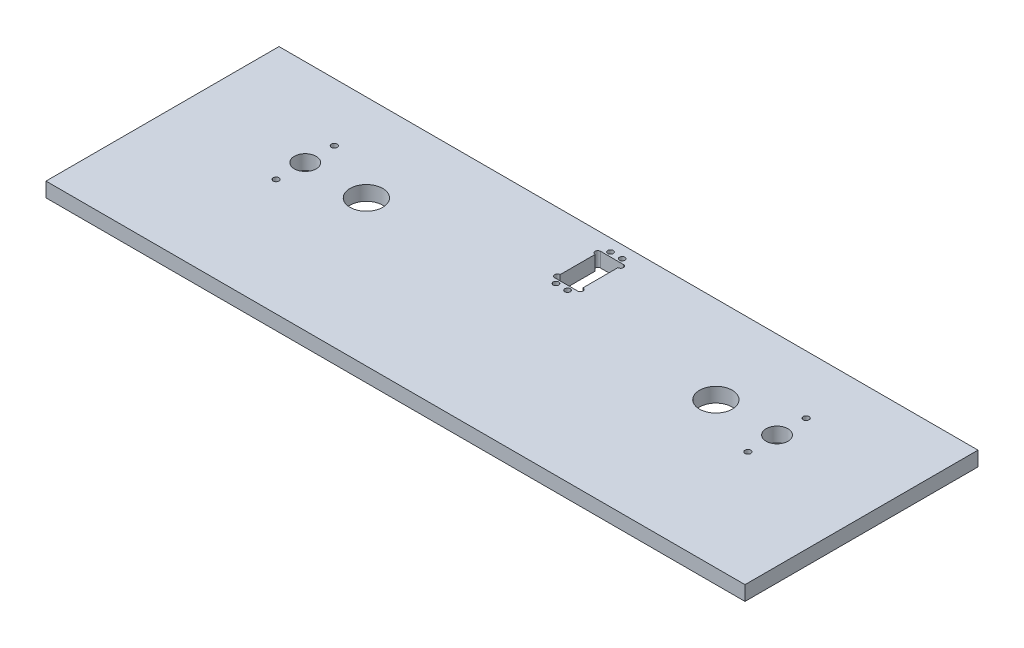
SolidWorks part; units mm, degrees
ref_plane "Front Plane" through (0, 0, 0) normal (0, 0, 1) x (1, 0, 0)
ref_plane "Top Plane" through (0, 0, 0) normal (0, 1, 0) x (1, 0, 0)
ref_plane "Right Plane" through (0, 0, 0) normal (1, 0, 0) x (0, 0, -1)
sketch "Sketch1" plane through (0, 0, 0) normal (0, 1, 0) x (1, 0, 0)
  line L0 (-53.34, 0) -> (-53.34, 25.4) construction
  line L1 (-53.34, 0) -> (-53.34, -25.4) construction
  line L2 (152.4, 51.221) -> (152.4, -51.2649) construction
  line L3 (-101.4095, -20.0025) -> (-101.4095, -9.652) construction
  line L4 (-111.379, -40.005) -> (-91.44, -40.005) construction
  line L5 (-111.379, -40.005) -> (-111.379, 0) construction
  line L6 (-111.379, 0) -> (-91.44, 0) construction
  line L7 (-91.44, -40.005) -> (-91.44, 0) construction
  line L8 (-111.379, -40.005) -> (-91.44, 0) construction
  line L9 (-111.379, 0) -> (-91.44, -40.005) construction
  line L10 (-106.4895, -43.815) -> (-96.3295, -43.815) construction
  line L11 (-106.4895, -43.815) -> (-106.4895, 3.81) construction
  line L12 (-106.4895, 3.81) -> (-96.3295, 3.81) construction
  line L13 (-96.3295, -43.815) -> (-96.3295, 3.81) construction
  line L14 (-106.4895, -43.815) -> (-96.3295, 3.81) construction
  line L15 (-106.4895, 3.81) -> (-96.3295, -43.815) construction
  line L16 (-82.3595, 11.7475) -> (-120.4595, 11.7475) construction
  line L17 (-82.3595, 11.7475) -> (-82.3595, -51.7525) construction
  line L18 (-82.3595, -51.7525) -> (-120.4595, -51.7525) construction
  line L19 (-120.4595, 11.7475) -> (-120.4595, -51.7525) construction
  line L21 (-152.4, 76.2) -> (152.4, 76.2)
  line L22 (-152.4, 76.2) -> (-152.4, -127)
  line L23 (-152.4, -127) -> (152.4, -127)
  line L24 (152.4, 76.2) -> (152.4, -127)
  circle A0 centre (0, 0) radius 14.2875
  circle A1 centre (0, 0) radius 45.72 construction
  circle A2 centre (-53.34, 0) radius 7.62 construction
  circle A3 centre (-53.34, 0) radius 9.525
  circle A4 centre (-53.34, 25.4) radius 2.54
  circle A5 centre (-53.34, -25.4) radius 2.54
  circle A6 centre (-96.3295, 3.81) radius 2.1844 construction
  circle A7 centre (-106.4895, 3.81) radius 2.1844 construction
  circle A8 centre (-106.4895, -43.815) radius 2.1844 construction
  circle A9 centre (-96.3295, -43.815) radius 2.1844 construction
  circle A10 centre (-53.34, 0) radius 31.75 construction
  point P13 (-101.4095, -20.0025)
  point P32 (-147.8387, 59.4419)
  point P38 (152.4, 80.9875)
  point P39 (133.2116, 76.2)
  point P40 (-111.379, 0)
  dimension "D1" = 28.575
  dimension "D2" = 91.44
  dimension "D3" = 15.24
  dimension "D4" = 19.05
  dimension "D5" = 5.08
  dimension "D12" = 4.3688
  dimension "D17" = 38.1
  dimension "D19" = 76.2
  dimension "D6" = 25.4
  dimension "D7" = 152.4
  dimension "D8" = 19.939
  dimension "D9" = 40.005
  dimension "D10" = 10.16
  dimension "D11" = 13.462
  dimension "D13" = 31.75
  dimension "D14" = 31.75
  dimension "D15" = 19.05
  dimension "D16" = 19.05
  dimension "D18" = 47.625
  dimension "D20" = 203.2
  dimension "D21" = 304.8
extrude "Boss-Extrude1" add sketch "Sketch1" along normal blind 12.7
sketch "Sketch2" plane through (0, 12.7, 0) normal (0, 1, 0) x (1, 0, 0)
  line L0 (-111.379, 0) -> (-111.379, -40.005) construction
  line L1 (-91.44, -40.005) -> (-91.44, 0) construction
  line L2 (-111.379, -40.005) -> (-111.379, -30.4546)
  line L3 (-111.379, -9.5504) -> (-111.379, 0)
  line L4 (-91.44, 0) -> (-91.44, -9.5504)
  line L5 (-91.44, -30.4546) -> (-91.44, -40.005)
  arc A0 (-111.379, -40.005) -> (-111.379, -30.4546) centre (-111.379, -35.2298) cw
  arc A1 (-91.44, -40.005) -> (-91.44, -30.4546) centre (-91.44, -35.2298) ccw
  arc A2 (-91.44, 0) -> (-91.44, -9.5504) centre (-91.44, -4.7752) cw
  arc A3 (-111.379, 0) -> (-111.379, -9.5504) centre (-111.379, -4.7752) ccw
  dimension "D1" = 4.7752
extrude "Cut-Extrude1" [suppressed] cut sketch "Sketch2" against normal through all
mirror "Mirror1" about plane through (152.4, 12.7, -76.2) normal (-1, 0, 0) of "Boss-Extrude1"
sketch "Sketch3" plane through (0, 12.7, 0) normal (0, 1, 0) x (1, 0, 0)
  line L0 (0, 0) -> (14.5961, 29.9264) construction
  line L1 (0, 0) -> (-32.0063, 9.1777) construction
  line L2 (0, 0) -> (-201.1255, 0) construction
  line L3 (152.4, 52.145) -> (177.8, 52.145) construction
  line L4 (152.4, 52.145) -> (127, 52.145) construction
  line L5 (177.8, 52.145) -> (14.5961, 29.9264)
  line L6 (127, 52.145) -> (-32.0063, 9.1777)
  line L7 (152.4, 76.2) -> (152.4, -127) construction
  point P7 (-55.4907, 34.7425)
  point P10 (-170.7043, 48.9487)
  point P11 (-158.1967, -69.0705)
  point P12 (-362.3113, 103.8911)
  point P13 (-157.8082, -67.2985)
  point P14 (-132.304, -57.3982)
  point P15 (-41.7778, -18.3478)
  point P16 (-118.0308, 2.0602)
  point P17 (-75.9965, -77.7334)
  point P18 (-16.6565, -40.7938)
  point P19 (-23.8604, -38.3154)
  point P20 (-26.0881, -12.8058)
  point P21 (-21.8494, -18.1068)
  point P22 (-97.8735, 0)
  point P23 (-35.1027, 42.2914)
  point P24 (115.3008, 48.8111)
  point P25 (85.4679, 33.0805)
  point P26 (-43.7192, 0)
  point P27 (127.7943, 26.1135)
  point P28 (151.7634, 31.6306)
  point P31 (0, 0)
  point P32 (152.4, 52.1666)
  dimension "D1" = 16
  dimension "D2" = 116
  dimension "D3" = 25.4
sketch "Sketch5" plane through (0, 12.7, 0) normal (0, 1, 0) x (1, 0, 0)
  line L0 (152.4, 41.7945) -> (152.4, 52.145) construction
  line L1 (142.4305, 21.792) -> (162.3695, 21.792)
  line L2 (142.4305, 26.5672) -> (142.4305, 57.0218)
  line L3 (142.4305, 61.797) -> (162.3695, 61.797)
  line L4 (162.3695, 26.5672) -> (162.3695, 57.0218)
  line L5 (142.4305, 21.792) -> (162.3695, 61.797) construction
  line L6 (142.4305, 61.797) -> (162.3695, 21.792) construction
  line L7 (147.32, 17.982) -> (157.48, 17.982) construction
  line L8 (147.32, 17.982) -> (147.32, 65.607) construction
  line L9 (147.32, 65.607) -> (157.48, 65.607) construction
  line L10 (157.48, 17.982) -> (157.48, 65.607) construction
  line L11 (147.32, 17.982) -> (157.48, 65.607) construction
  line L12 (147.32, 65.607) -> (157.48, 17.982) construction
  line L17 (152.4, 76.2) -> (152.4, -127) construction
  circle A0 centre (157.48, 65.607) radius 2.3838
  circle A1 centre (147.32, 65.607) radius 2.3838
  circle A2 centre (147.32, 17.982) radius 2.3838
  circle A3 centre (157.48, 17.982) radius 2.3838
  arc A4 (142.4305, 61.797) -> (142.4305, 57.0218) centre (142.4305, 59.4094) ccw
  arc A5 (142.4305, 21.792) -> (142.4305, 26.5672) centre (142.4305, 24.1796) cw
  arc A6 (162.3695, 21.792) -> (162.3695, 26.5672) centre (162.3695, 24.1796) ccw
  arc A7 (162.3695, 61.797) -> (162.3695, 57.0218) centre (162.3695, 59.4094) cw
  point P0 (152.4, 41.7945)
  point P26 (162.3695, 27.8841)
  point P27 (142.4305, 27.1731)
  point P28 (162.3695, 26.5672)
  point P29 (162.3695, 31.3424)
  point P30 (0, 0)
  point P31 (0, 0)
  point P32 (0, 0)
  point P33 (142.4305, 52.145)
  point P34 (142.4305, 31.3424)
  point P35 (142.4305, 26.5672)
  point P36 (142.4305, 21.792)
  dimension "D5" = 4.7676
  dimension "D6" = 2.3876
  dimension "D1" = 19.939
  dimension "D2" = 40.005
  dimension "D3" = 10.16
  dimension "D4" = 13.462
  dimension "D8" = 47.625
extrude "Cut-Extrude2" cut sketch "Sketch5" against normal through all
